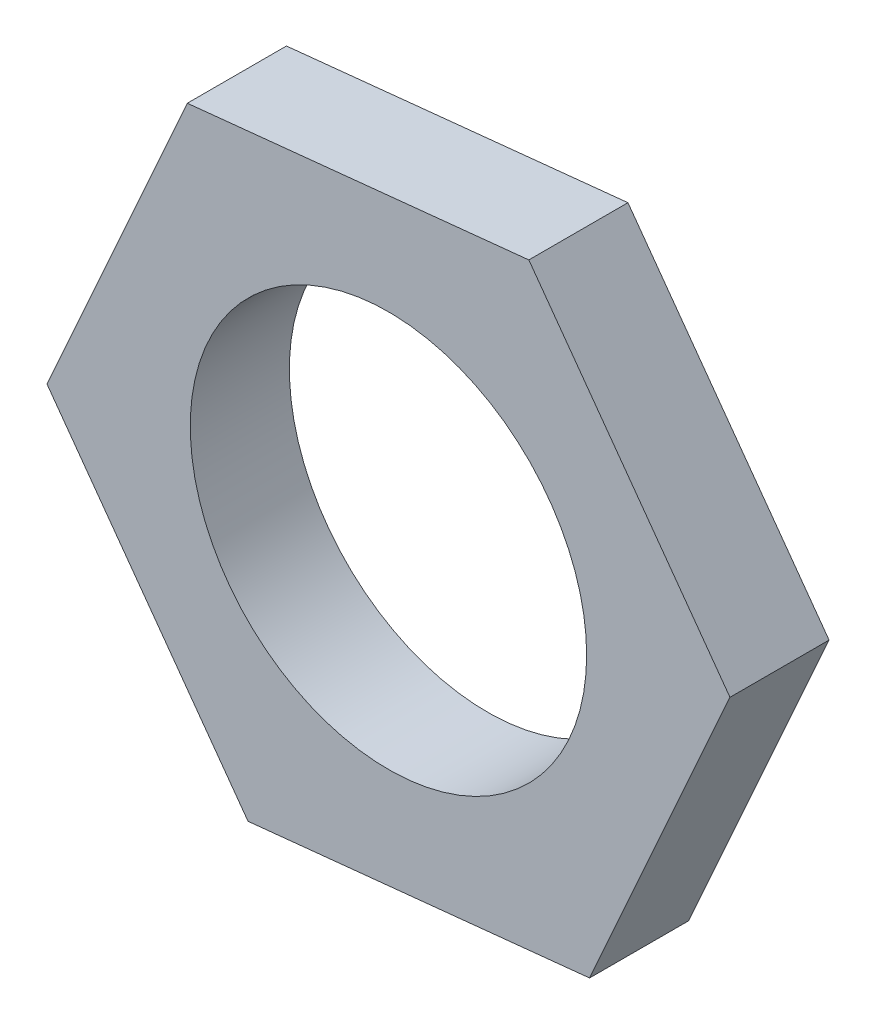
SolidWorks part; units mm, degrees
ref_plane "Front Plane" through (0, 0, 0) normal (0, 0, 1) x (1, 0, 0)
ref_plane "Top Plane" through (0, 0, 0) normal (0, 1, 0) x (1, 0, 0)
ref_plane "Right Plane" through (0, 0, 0) normal (1, 0, 0) x (0, 0, -1)
sketch "Sketch1" plane through (0, 0, 0) normal (0, 0, 1) x (1, 0, 0)
  line L1 (0.5074, -0.7018) -> (0.8615, 0.0885)
  line L2 (0.8615, 0.0885) -> (0.3541, 0.7903)
  line L3 (0.3541, 0.7903) -> (-0.5074, 0.7018)
  line L4 (-0.5074, 0.7018) -> (-0.8615, -0.0885)
  line L5 (-0.8615, -0.0885) -> (-0.3541, -0.7903)
  line L6 (-0.3541, -0.7903) -> (0.5074, -0.7018)
  circle A0 centre (0, 0) radius 0.5
  circle A1 centre (0, 0) radius 0.75 construction
  dimension "D1" = 1
  dimension "D2" = 1.5
extrude "Boss-Extrude1" add sketch "Sketch1" along normal blind 0.25
